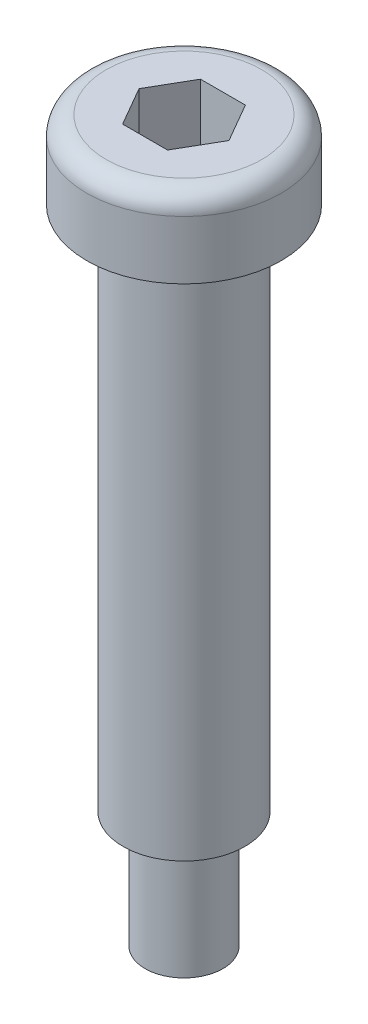
SolidWorks part; units mm, degrees
ref_plane "Front Plane" through (0, 0, 0) normal (0, 0, 1) x (1, 0, 0)
ref_plane "Top Plane" through (0, 0, 0) normal (0, 1, 0) x (1, 0, 0)
ref_plane "Right Plane" through (0, 0, 0) normal (1, 0, 0) x (0, 0, -1)
sketch "Sketch1" plane through (0, 0, 0) normal (0, 0, 1) x (1, 0, 0)
  line L0 (0, 0) -> (-2, 0)
  line L1 (-2, 0) -> (-2, 6)
  line L2 (-2, 6) -> (-3.13, 6)
  line L3 (-3.13, 6) -> (-3.13, 33)
  line L4 (-3.13, 33) -> (-5, 33)
  line L5 (-5, 33) -> (-5, 37)
  line L6 (-5, 37) -> (0, 37)
  line L7 (0, 37) -> (0, 0)
  dimension "D1" = 5
  dimension "D2" = 3.13
  dimension "D3" = 2
  dimension "D4" = 6
  dimension "D5" = 37
  dimension "D6" = 4
revolve "Revolve1" add sketch "Sketch1" angle 360 about L7
sketch "Sketch2" plane through (0, 37, 0) normal (0, 1, 0) x (1, 0, 0)
  line L1 (-1.1547, -2) -> (1.1547, -2)
  line L2 (1.1547, -2) -> (2.3094, 0)
  line L3 (2.3094, 0) -> (1.1547, 2)
  line L4 (1.1547, 2) -> (-1.1547, 2)
  line L5 (-1.1547, 2) -> (-2.3094, 0)
  line L6 (-2.3094, 0) -> (-1.1547, -2)
  circle A0 centre (0, 0) radius 2 construction
  dimension "D1" = 4
extrude "Cut-Extrude1" cut sketch "Sketch2" against normal blind 3
fillet "Fillet1" radius 1 1 edges at (-5, 37, 0)
